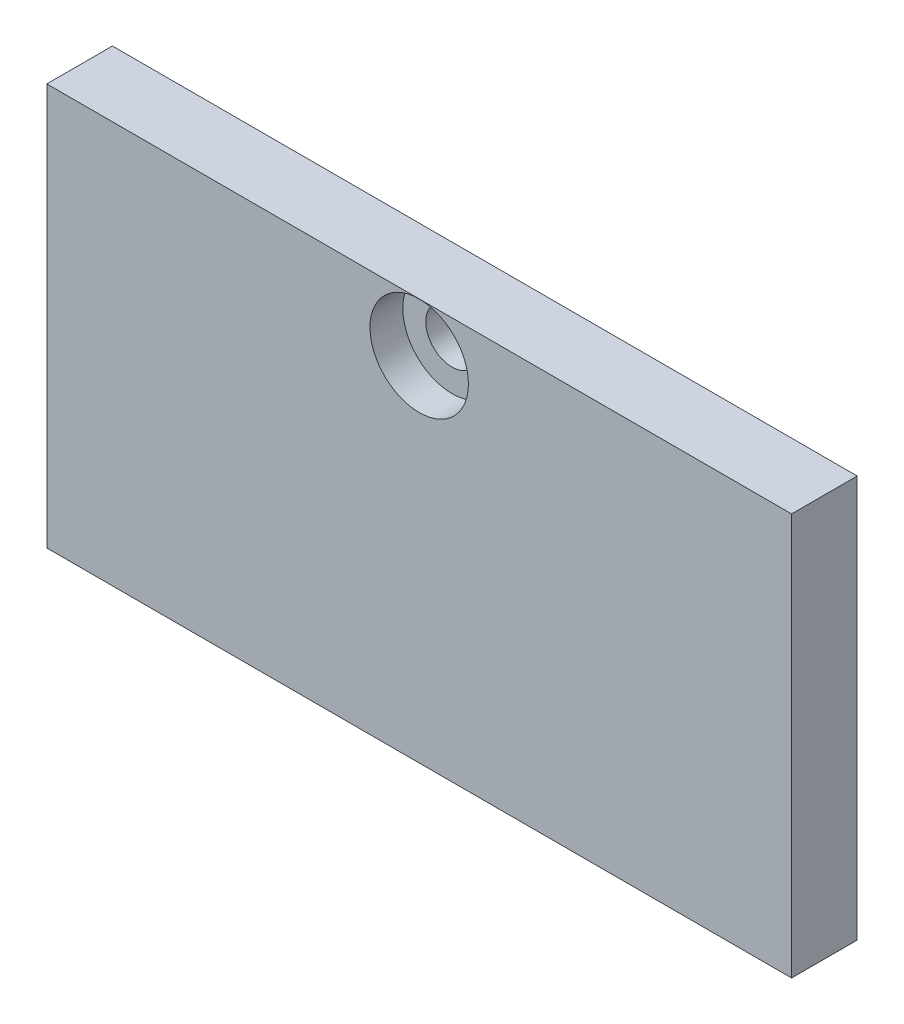
SolidWorks part; units mm, degrees
ref_plane "前视基准面" through (0, 0, 0) normal (0, 0, 1) x (1, 0, 0)
ref_plane "上视基准面" through (0, 0, 0) normal (0, 1, 0) x (1, 0, 0)
ref_plane "右视基准面" through (0, 0, 0) normal (1, 0, 0) x (0, 0, -1)
sketch "草图1" plane through (0, 0, 0) normal (0, 0, 1) x (1, 0, 0)
  line L9 (-76.4538, 38.217) -> (-31.0538, 38.217)
  line L10 (-76.4538, 38.217) -> (-76.4538, 13.717)
  line L11 (-76.4538, 13.717) -> (-31.0538, 13.717)
  line L12 (-31.0538, 38.217) -> (-31.0538, 13.717)
  dimension "D1" = 45.4
  dimension "D2" = 24.5
extrude "凸台-拉伸1" add sketch "草图1" along normal blind 4
sketch "草图2" plane through (0, 0, 4) normal (0, 0, 1) x (1, 0, 0)
  line L0 (-31.0538, 38.217) -> (-76.4538, 38.217) construction
  line L2 (-76.4538, 13.717) -> (-31.0538, 13.717) construction
  circle A0 centre (-53.7538, 35.217) radius 1.6
  point P6 (-53.7538, 13.717)
  dimension "D1" = 3.2
  dimension "D2" = 3
  dimension "D3" = 0
extrude "切除-拉伸1" cut sketch "草图2" against normal through all
sketch "草图3" plane through (0, 0, 4) normal (0, 0, 1) x (1, 0, 0)
  line L3 (-54.0634, 38.201) -> (-53.4865, 38.2051)
  arc A0 (-54.0634, 38.201) -> (-53.4865, 38.2051) centre (-53.7538, 35.217) ccw
  dimension "D1" = 6
extrude "切除-拉伸2" cut sketch "草图3" against normal blind 2
sketch "草图4" plane through (0, 0, 0) normal (0, 0, -1) x (-1, 0, 0)
  line L0 (76.4538, 13.717) -> (31.0538, 13.717) construction
  line L1 (47.5038, -4.283) -> (60.0038, -4.283)
  line L2 (47.5038, -4.283) -> (47.5038, 31.717)
  line L3 (47.5038, 31.717) -> (60.0038, 31.717)
  line L4 (60.0038, -4.283) -> (60.0038, 31.717)
  line L5 (47.5038, -4.283) -> (60.0038, 31.717) construction
  line L6 (47.5038, 31.717) -> (60.0038, -4.283) construction
  point P0 (53.7538, 13.717)
  dimension "D1" = 36
  dimension "D2" = 12.5
extrude "切除-拉伸3" cut sketch "草图4" against normal blind 3.2
sketch "草图5" plane through (0, 0, 0) normal (0, 0, -1) x (-1, 0, 0)
  line L0 (31.0538, 38.217) -> (76.4538, 38.217) construction
  line L1 (53.7538, 38.217) -> (53.7538, 13.717) construction
  line L2 (60.0038, 13.717) -> (47.5038, 13.717) construction
  circle A0 centre (44.469, 31.5031) radius 2.9
  circle A1 centre (53.7538, 35.217) radius 1.6 construction
  circle A2 centre (63.0386, 31.5031) radius 2.9
  dimension "D1" = 5.8
  dimension "D2" = 10
extrude "凸台-拉伸2" add sketch "草图5" along normal blind 1.7
